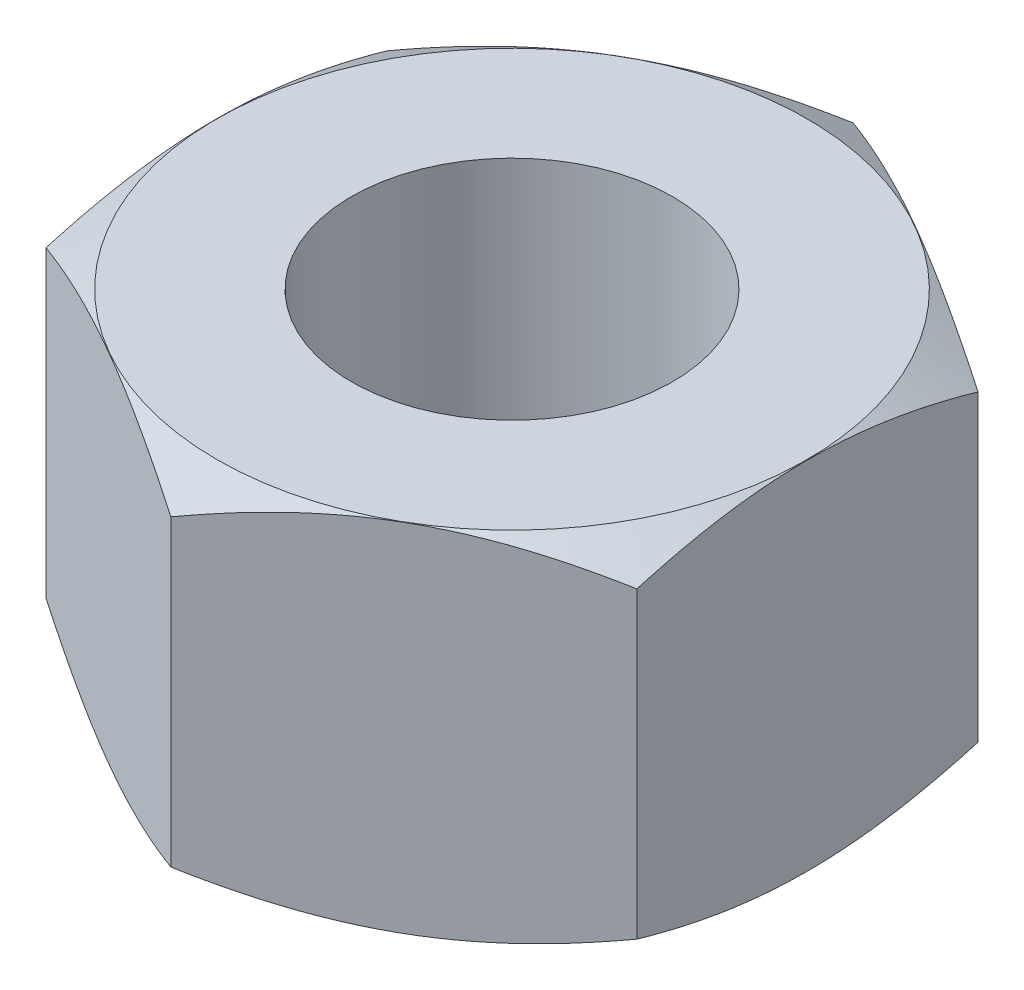
SolidWorks part; units mm, degrees
material "1.0035 (S185)"
ref_plane "Płaszczyzna przednia" through (0, 0, 0) normal (0, 0, 1) x (1, 0, 0)
ref_plane "Płaszczyzna górna" through (0, 0, 0) normal (0, 1, 0) x (1, 0, 0)
ref_plane "Płaszczyzna prawa" through (0, 0, 0) normal (1, 0, 0) x (0, 0, -1)
sketch "Szkic1" plane through (0, 0, 0) normal (0, 0, 1) x (1, 0, 0)
  line L0 (0, 0) -> (0, 36.0407) construction
  line L2 (4.188, 0) -> (8.9, 0)
  line L3 (4.188, 0) -> (4.188, 9.3)
  line L4 (4.188, 9.3) -> (8.9, 9.3)
  line L5 (8.9, 0) -> (8.9, 9.3)
  dimension "D1" = 8.376
  dimension "D2" = 9.3
  dimension "D3" = 17.8
revolve "Obrót1" add sketch "Szkic1" angle 360 about L0
cosmetic thread "Oznaczenie gwintu1" parameters "D2"=10
chamfer "Sfazowanie1" distance 1.2 angle 30 2 edges at (0, 9.3, -8.9) (0, 0, -8.9)
sketch "Szkic2" plane through (0, 9.3, 0) normal (0, 1, 0) x (1, 0, 0)
  line L1 (7.7076, 4.45) -> (0, 8.9)
  line L2 (0, 8.9) -> (-7.7076, 4.45)
  line L3 (-7.7076, 4.45) -> (-7.7076, -4.45)
  line L4 (-7.7076, -4.45) -> (0, -8.9)
  line L5 (0, -8.9) -> (7.7076, -4.45)
  line L6 (7.7076, -4.45) -> (7.7076, 4.45)
  circle A0 centre (0, 0) radius 7.7076 construction
  circle A1 centre (0, 0) radius 8.9 construction
extrude "Wytnij-wyciągnięcie1" cut sketch "Szkic2" against normal through all flip side to cut
